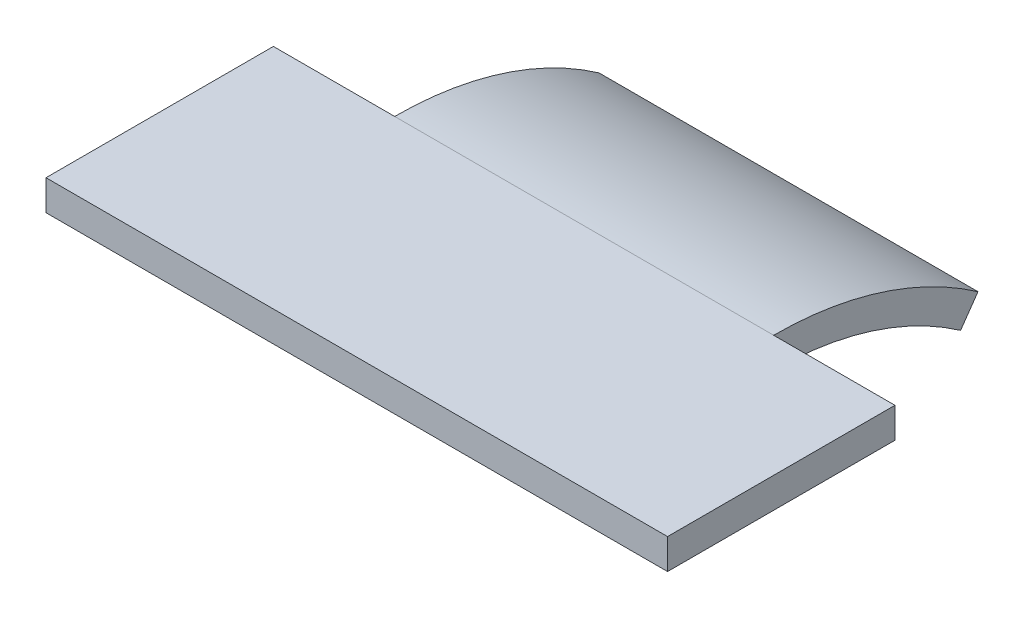
SolidWorks part; units mm, degrees
ref_plane "Piano frontale" through (0, 0, 0) normal (0, 0, 1) x (1, 0, 0)
ref_plane "Piano superiore" through (0, 0, 0) normal (0, 1, 0) x (1, 0, 0)
ref_plane "Piano destro" through (0, 0, 0) normal (1, 0, 0) x (0, 0, -1)
sketch "Schizzo1" plane through (0, 0, 0) normal (1, 0, 0) x (0, 0, -1)
  line L1 (0, 47) -> (-30, 47)
  line L2 (0, 0) -> (0, 47) construction
  line L3 (0, 0) -> (26.9581, 38.5001) construction
  line L4 (0, 43) -> (-30, 43)
  line L7 (-30, 47) -> (-30, 43)
  line L8 (24.6638, 35.2235) -> (26.9581, 38.5001)
  arc A0 (26.9581, 38.5001) -> (0, 47) centre (0, 0) ccw
  arc A1 (24.6638, 35.2235) -> (0, 43) centre (0, 0) ccw
  dimension "D1" = 94
  dimension "D3" = 4
  dimension "D2" = 35
  dimension "D4" = 30
extrude "Estrusione-Estrusione1" add sketch "Schizzo1" along normal blind 82
sketch "Schizzo2" plane through (0, 47, 0) normal (0, 1, 0) x (1, 0, 0)
  line L0 (16, 0) -> (16, 26.9581)
  line L1 (82, -30) -> (0, -30) construction
  line L2 (82, 26.9581) -> (0, 26.9581) construction
  line L3 (66, 0) -> (66, 26.9581)
  line L4 (16, -30) -> (66, -30) construction
  line L5 (0, 0) -> (16, 0)
  line L6 (82, 0) -> (0, 0) construction
  line L7 (66, 0) -> (82, 0)
  line L8 (66, 26.9581) -> (82, 26.9581)
  line L9 (82, 26.9581) -> (82, 0)
  line L10 (0, 0) -> (0, 26.9581)
  line L11 (0, 26.9581) -> (16, 26.9581)
  line L12 (16, -30) -> (16, 0) construction
  line L13 (66, -30) -> (66, 0) construction
  point P8 (41, -30)
  point P10 (41, -30)
  dimension "D1" = 50
extrude "Taglio-Estrusione1" cut sketch "Schizzo2" against normal blind 20
